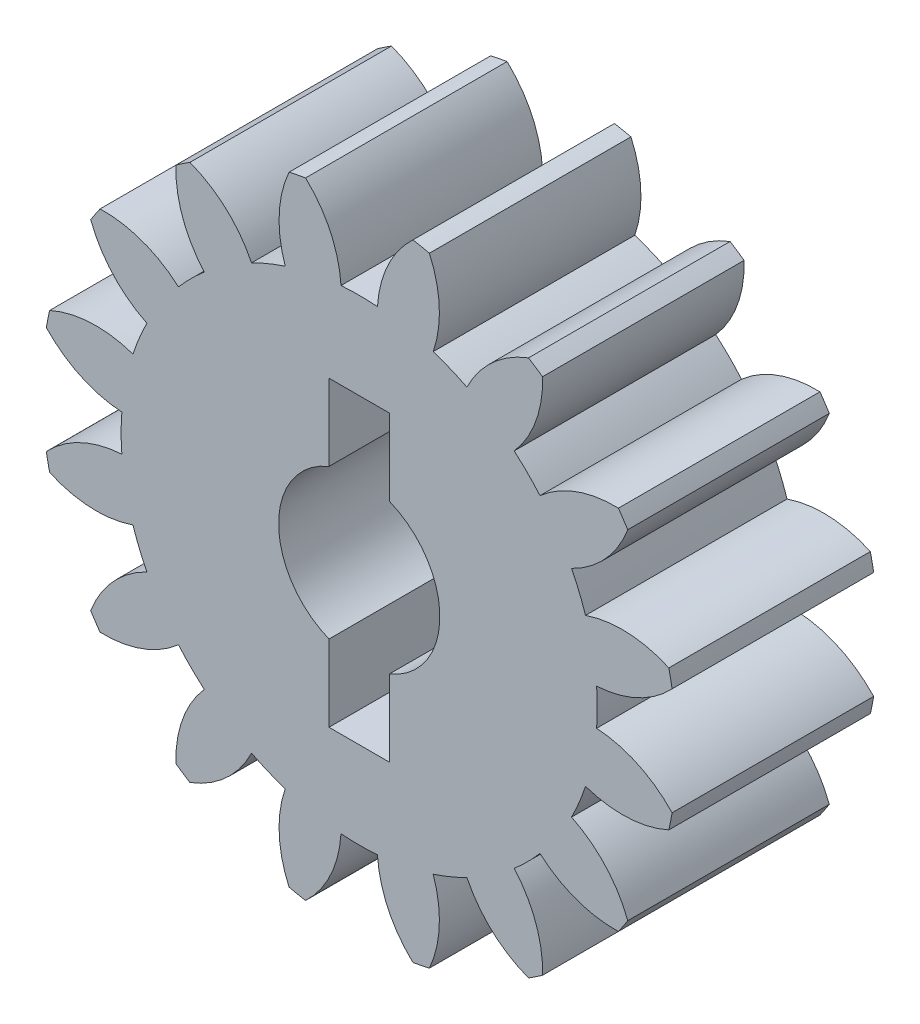
SolidWorks part; units mm, degrees
ref_plane "Front Plane" through (0, 0, 0) normal (0, 0, 1) x (1, 0, 0)
ref_plane "Top Plane" through (0, 0, 0) normal (0, 1, 0) x (1, 0, 0)
ref_plane "Right Plane" through (0, 0, 0) normal (1, 0, 0) x (0, 0, -1)
sketch "Sketch1" plane through (0, 0, 0) normal (0, 0, 1) x (1, 0, 0)
  line L0 (-3, 15) -> (3, 15)
  line L1 (-3, 15) -> (-3, 7.4162)
  line L2 (-3, -15) -> (3, -15)
  line L3 (3, 15) -> (3, 7.4162)
  line L6 (3, -7.4162) -> (3, -15)
  line L9 (-3, -7.4162) -> (-3, -15)
  arc A0 (-31.0469, 5.3236) -> (-23.5546, 1.8098) centre (-22.8815, 12.9895) ccw
  arc A1 (-23.5546, 1.8098) -> (-23.5546, -1.8098) centre (0, 0) ccw
  arc A2 (-23.5546, -1.8098) -> (-31.0469, -5.3236) centre (-22.8815, -12.9895) ccw
  arc A3 (-31.0469, -5.3236) -> (-30.7208, -6.9627) centre (0, 0) ccw
  arc A4 (-30.7208, -6.9627) -> (-22.4542, -7.3419) centre (-26.1106, 3.2444) ccw
  arc A5 (-22.4542, -7.3419) -> (-21.069, -10.686) centre (0, 0) ccw
  arc A6 (-21.069, -10.686) -> (-26.6463, -16.7995) centre (-16.1688, -20.7571) ccw
  arc A7 (-26.6463, -16.7995) -> (-25.7178, -18.1891) centre (0, 0) ccw
  arc A8 (-25.7178, -18.1891) -> (-17.9353, -15.3759) centre (-25.3646, -6.9947) ccw
  arc A9 (-17.9353, -15.3759) -> (-15.3759, -17.9353) centre (0, 0) ccw
  arc A10 (-15.3759, -17.9353) -> (-18.1891, -25.7178) centre (-6.9947, -25.3646) ccw
  arc A11 (-18.1891, -25.7178) -> (-16.7995, -26.6463) centre (0, 0) ccw
  arc A12 (-16.7995, -26.6463) -> (-10.686, -21.069) centre (-20.7571, -16.1688) ccw
  arc A13 (-10.686, -21.069) -> (-7.3419, -22.4542) centre (0, 0) ccw
  arc A14 (-7.3419, -22.4542) -> (-6.9627, -30.7208) centre (3.2444, -26.1106) ccw
  arc A15 (-6.9627, -30.7208) -> (-5.3236, -31.0469) centre (0, 0) ccw
  arc A16 (-5.3236, -31.0469) -> (-1.8098, -23.5546) centre (-12.9895, -22.8815) ccw
  arc A17 (-1.8098, -23.5546) -> (1.8098, -23.5546) centre (0, 0) ccw
  arc A18 (1.8098, -23.5546) -> (5.3236, -31.0469) centre (12.9895, -22.8815) ccw
  arc A19 (5.3236, -31.0469) -> (6.9627, -30.7208) centre (0, 0) ccw
  arc A20 (6.9627, -30.7208) -> (7.3419, -22.4542) centre (-3.2444, -26.1106) ccw
  arc A21 (7.3419, -22.4542) -> (10.686, -21.069) centre (0, 0) ccw
  arc A22 (10.686, -21.069) -> (16.7995, -26.6463) centre (20.7571, -16.1688) ccw
  arc A23 (16.7995, -26.6463) -> (18.1891, -25.7178) centre (0, 0) ccw
  arc A24 (18.1891, -25.7178) -> (15.3759, -17.9353) centre (6.9947, -25.3646) ccw
  arc A25 (15.3759, -17.9353) -> (17.9353, -15.3759) centre (0, 0) ccw
  arc A26 (17.9353, -15.3759) -> (25.7178, -18.1891) centre (25.3646, -6.9947) ccw
  arc A27 (25.7178, -18.1891) -> (26.6463, -16.7995) centre (0, 0) ccw
  arc A28 (26.6463, -16.7995) -> (21.069, -10.686) centre (16.1688, -20.7571) ccw
  arc A29 (21.069, -10.686) -> (22.4542, -7.3419) centre (0, 0) ccw
  arc A30 (22.4542, -7.3419) -> (30.7208, -6.9627) centre (26.1106, 3.2444) ccw
  arc A31 (30.7208, -6.9627) -> (31.0469, -5.3236) centre (0, 0) ccw
  arc A32 (31.0469, -5.3236) -> (23.5546, -1.8098) centre (22.8815, -12.9895) ccw
  arc A33 (23.5546, -1.8098) -> (23.5546, 1.8098) centre (0, 0) ccw
  arc A34 (23.5546, 1.8098) -> (31.0469, 5.3236) centre (22.8815, 12.9895) ccw
  arc A35 (31.0469, 5.3236) -> (30.7208, 6.9627) centre (0, 0) ccw
  arc A36 (30.7208, 6.9627) -> (22.4542, 7.3419) centre (26.1106, -3.2444) ccw
  arc A37 (22.4542, 7.3419) -> (21.069, 10.686) centre (0, 0) ccw
  arc A38 (21.069, 10.686) -> (26.6463, 16.7995) centre (16.1688, 20.7571) ccw
  arc A39 (26.6463, 16.7995) -> (25.7178, 18.1891) centre (0, 0) ccw
  arc A40 (25.7178, 18.1891) -> (17.9353, 15.3759) centre (25.3646, 6.9947) ccw
  arc A41 (17.9353, 15.3759) -> (15.3759, 17.9353) centre (0, 0) ccw
  arc A42 (15.3759, 17.9353) -> (18.1891, 25.7178) centre (6.9947, 25.3646) ccw
  arc A43 (18.1891, 25.7178) -> (16.7995, 26.6463) centre (0, 0) ccw
  arc A44 (16.7995, 26.6463) -> (10.686, 21.069) centre (20.7571, 16.1688) ccw
  arc A45 (10.686, 21.069) -> (7.3419, 22.4542) centre (0, 0) ccw
  arc A46 (7.3419, 22.4542) -> (6.9627, 30.7208) centre (-3.2444, 26.1106) ccw
  arc A47 (6.9627, 30.7208) -> (5.3236, 31.0469) centre (0, 0) ccw
  arc A48 (5.3236, 31.0469) -> (1.8098, 23.5546) centre (12.9895, 22.8815) ccw
  arc A49 (1.8098, 23.5546) -> (-1.8098, 23.5546) centre (0, 0) ccw
  arc A50 (-1.8098, 23.5546) -> (-5.3236, 31.0469) centre (-12.9895, 22.8815) ccw
  arc A51 (-5.3236, 31.0469) -> (-6.9627, 30.7208) centre (0, 0) ccw
  arc A52 (-6.9627, 30.7208) -> (-7.3419, 22.4542) centre (3.2444, 26.1106) ccw
  arc A53 (-7.3419, 22.4542) -> (-10.686, 21.069) centre (0, 0) ccw
  arc A54 (-10.686, 21.069) -> (-16.7995, 26.6463) centre (-20.7571, 16.1688) ccw
  arc A55 (-16.7995, 26.6463) -> (-18.1891, 25.7178) centre (0, 0) ccw
  arc A56 (-18.1891, 25.7178) -> (-15.3759, 17.9353) centre (-6.9947, 25.3646) ccw
  arc A57 (-15.3759, 17.9353) -> (-17.9353, 15.3759) centre (0, 0) ccw
  arc A58 (-17.9353, 15.3759) -> (-25.7178, 18.1891) centre (-25.3646, 6.9947) ccw
  arc A59 (-25.7178, 18.1891) -> (-26.6463, 16.7995) centre (0, 0) ccw
  arc A60 (-26.6463, 16.7995) -> (-21.069, 10.686) centre (-16.1688, 20.7571) ccw
  arc A61 (-21.069, 10.686) -> (-22.4542, 7.3419) centre (0, 0) ccw
  arc A62 (-22.4542, 7.3419) -> (-30.7208, 6.9627) centre (-26.1106, -3.2444) ccw
  arc A63 (-30.7208, 6.9627) -> (-31.0469, 5.3236) centre (0, 0) ccw
  arc A64 (-3, 7.4162) -> (-3, -7.4162) centre (0, 0) ccw
  arc A65 (3, -7.4162) -> (3, 7.4162) centre (0, 0) ccw
  point P4 (0, 0)
  point P128 (0, 0)
  point P129 (0, 0)
  point P135 (-7.8101, 22.4542)
  point P139 (0, 0)
  point P140 (-11.1542, 21.069)
  point P143 (0, 0)
  point P144 (0, 0)
  point P145 (0, 0)
  point P146 (0, 0)
  point P147 (0, 0)
  point P148 (0, 0)
  point P149 (0, 0)
  point P150 (0, 0)
  point P151 (0, 0)
  point P152 (0, 0)
  point P153 (0, 0)
  point P154 (0, 0)
  point P155 (6.8737, 22.4542)
  point P156 (6.5265, 30.7208)
  point P157 (0, 0)
  point P158 (0, 0)
  point P159 (0, 0)
  point P160 (0, 0)
  point P161 (0, 0)
  dimension "D3" = 16
  dimension "D4" = 3.6196
  dimension "D5" = 1.8098
  dimension "D6" = 1.6391
  dimension "D7" = 11.2
  dimension "D8" = 23.5546
  dimension "D9" = 1.6712
  dimension "D1" = 30
  dimension "D2" = 6
  dimension "D10" = 8.2667
  dimension "D13" = 7.4923
extrude "Boss-Extrude1" add sketch "Sketch1" along normal blind 20
